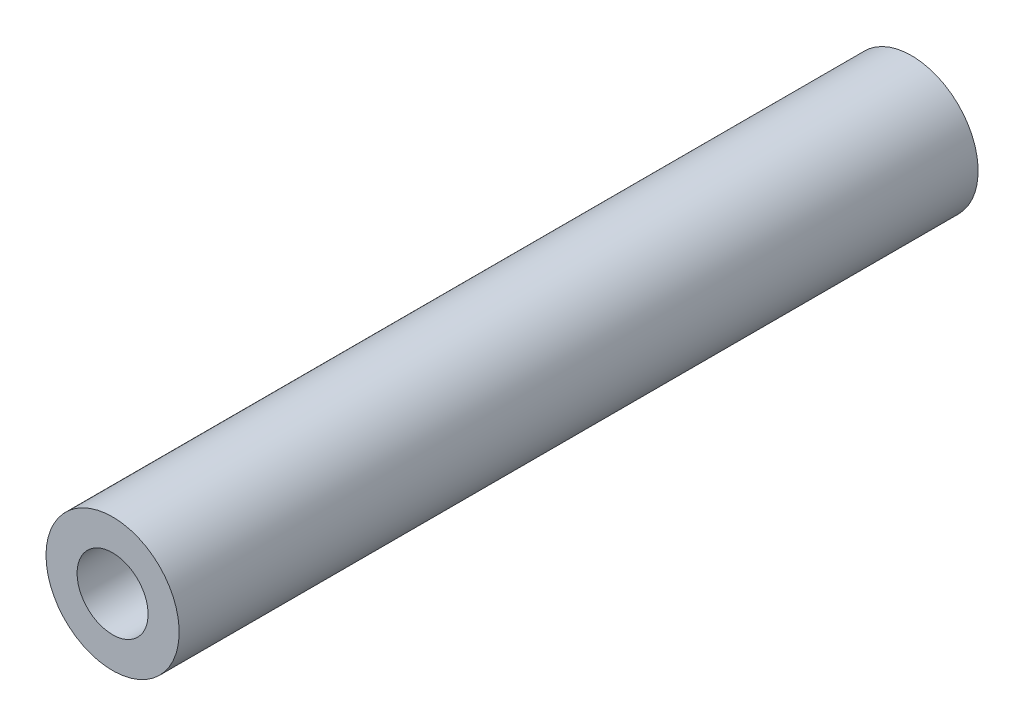
SolidWorks part; units mm, degrees
ref_plane "Front Plane" through (0, 0, 0) normal (0, 0, 1) x (1, 0, 0)
ref_plane "Top Plane" through (0, 0, 0) normal (0, 1, 0) x (1, 0, 0)
ref_plane "Right Plane" through (0, 0, 0) normal (1, 0, 0) x (0, 0, -1)
sketch "Sketch1" plane through (0, 0, 0) normal (0, 0, 1) x (1, 0, 0)
  circle A0 centre (0, 0) radius 15
  circle A1 centre (0, 0) radius 8
  dimension "D1" = 30
  dimension "D2" = 7
extrude "Boss-Extrude1" add sketch "Sketch1" along normal blind 180
